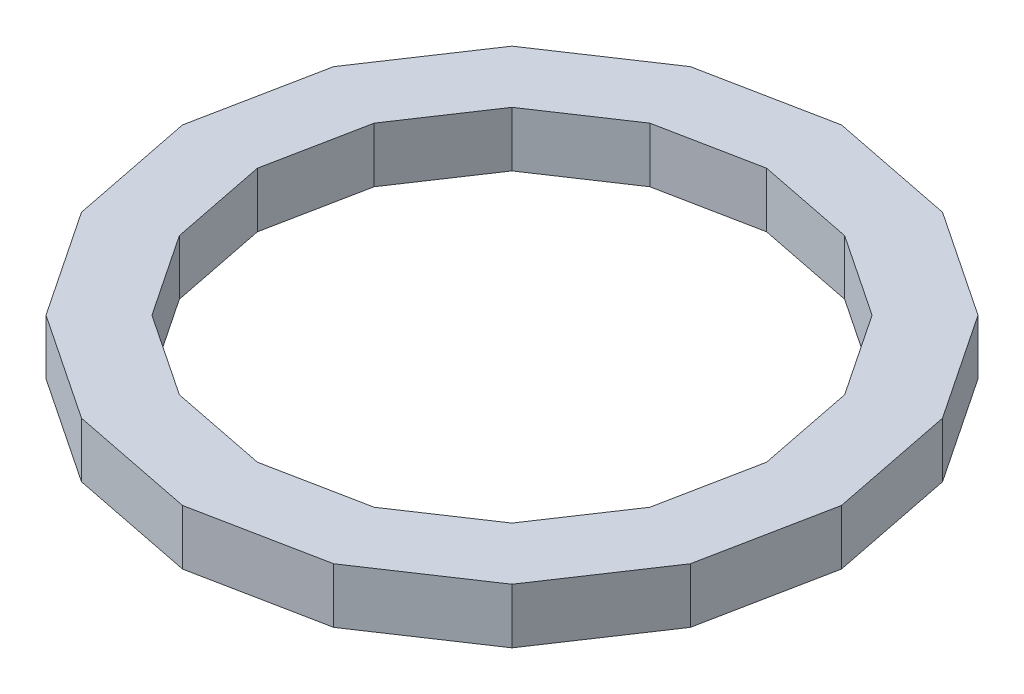
SolidWorks part; units mm, degrees
ref_plane "Front Plane" through (0, 0, 0) normal (0, 0, 1) x (1, 0, 0)
ref_plane "Top Plane" through (0, 0, 0) normal (0, 1, 0) x (1, 0, 0)
ref_plane "Right Plane" through (0, 0, 0) normal (1, 0, 0) x (0, 0, -1)
sketch "Sketch1" plane through (0, 0, 0) normal (0, 1, 0) x (1, 0, 0)
  line L1 (88.024, 0) -> (81.3236, 33.6853)
  line L2 (81.3236, 33.6853) -> (62.2424, 62.2424)
  line L3 (62.2424, 62.2424) -> (33.6853, 81.3236)
  line L4 (33.6853, 81.3236) -> (0, 88.024)
  line L5 (0, 88.024) -> (-33.6853, 81.3236)
  line L6 (-33.6853, 81.3236) -> (-62.2424, 62.2424)
  line L7 (-62.2424, 62.2424) -> (-81.3236, 33.6853)
  line L8 (-81.3236, 33.6853) -> (-88.024, 0)
  line L9 (-88.024, 0) -> (-81.3236, -33.6853)
  line L10 (-81.3236, -33.6853) -> (-62.2424, -62.2424)
  line L11 (-62.2424, -62.2424) -> (-33.6853, -81.3236)
  line L12 (-33.6853, -81.3236) -> (0, -88.024)
  line L13 (0, -88.024) -> (33.6853, -81.3236)
  line L14 (33.6853, -81.3236) -> (62.2424, -62.2424)
  line L15 (62.2424, -62.2424) -> (81.3236, -33.6853)
  line L16 (81.3236, -33.6853) -> (88.024, 0)
  line L17 (113.9216, 0) -> (105.2498, 43.5959)
  line L18 (105.2498, 43.5959) -> (80.5547, 80.5547)
  line L19 (80.5547, 80.5547) -> (43.5959, 105.2498)
  line L20 (43.5959, 105.2498) -> (0, 113.9216)
  line L21 (0, 113.9216) -> (-43.5959, 105.2498)
  line L22 (-43.5959, 105.2498) -> (-80.5547, 80.5547)
  line L23 (-80.5547, 80.5547) -> (-105.2498, 43.5959)
  line L24 (-105.2498, 43.5959) -> (-113.9216, 0)
  line L25 (-113.9216, 0) -> (-105.2498, -43.5959)
  line L26 (-105.2498, -43.5959) -> (-80.5547, -80.5547)
  line L27 (-80.5547, -80.5547) -> (-43.5959, -105.2498)
  line L28 (-43.5959, -105.2498) -> (0, -113.9216)
  line L29 (0, -113.9216) -> (43.5959, -105.2498)
  line L30 (43.5959, -105.2498) -> (80.5547, -80.5547)
  line L31 (80.5547, -80.5547) -> (105.2498, -43.5959)
  line L32 (105.2498, -43.5959) -> (113.9216, 0)
  circle A0 centre (0, 0) radius 86.3326 construction
  circle A1 centre (0, 0) radius 111.7326 construction
  dimension "D1" = 25.4
  dimension "D2" = 44.45
extrude "Boss-Extrude1" add sketch "Sketch1" along normal blind 19.05
